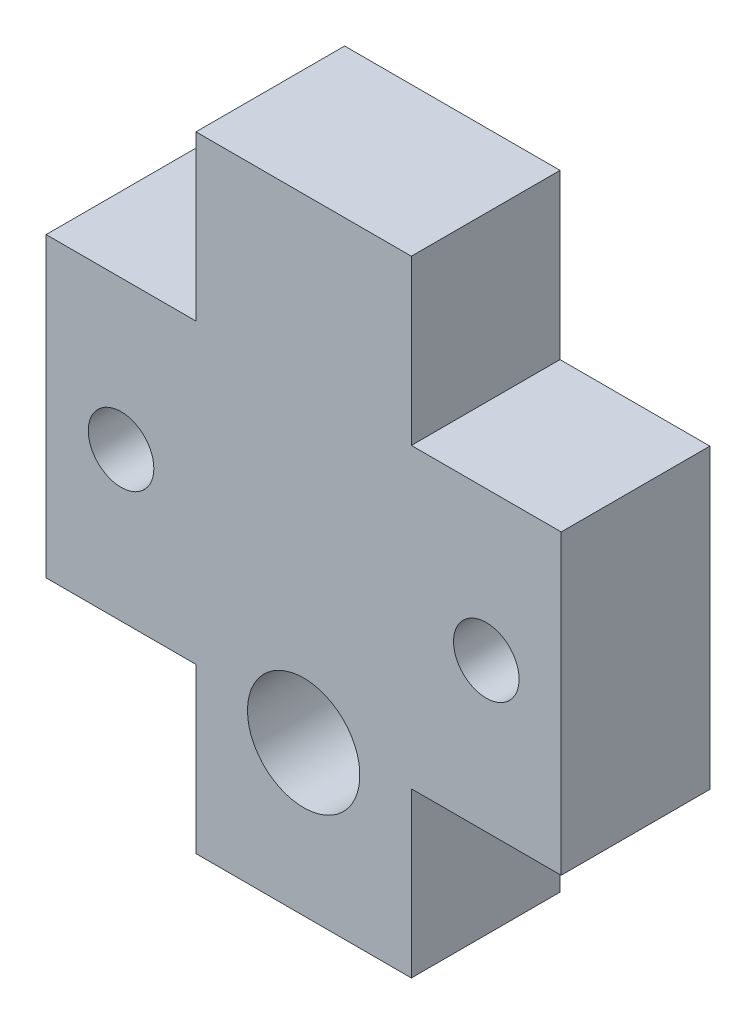
SolidWorks part; units mm, degrees
ref_plane "Front Plane" through (0, 0, 0) normal (0, 0, 1) x (1, 0, 0)
ref_plane "Top Plane" through (0, 0, 0) normal (0, 1, 0) x (1, 0, 0)
ref_plane "Right Plane" through (0, 0, 0) normal (1, 0, 0) x (0, 0, -1)
sketch "Sketch1" plane through (0, 0, 0) normal (0, 0, 1) x (1, 0, 0)
  line L0 (-11, 6.35) -> (-4.6, 6.35)
  line L1 (4.6, -13.35) -> (-4.6, -13.35)
  line L2 (4.6, -13.35) -> (4.6, 13.35)
  line L3 (4.6, 13.35) -> (-4.6, 13.35)
  line L4 (-4.6, -13.35) -> (-4.6, 13.35)
  line L5 (4.6, -13.35) -> (-4.6, 13.35) construction
  line L6 (4.6, 13.35) -> (-4.6, -13.35) construction
  line L7 (4.6, 6.35) -> (11, 6.35)
  line L9 (-4.6, -6.35) -> (-11, -6.35)
  line L10 (-11, 6.35) -> (-11, -6.35)
  line L13 (4.6, -6.35) -> (11, -6.35)
  line L14 (11, 6.35) -> (11, -6.35)
  circle A1 centre (-7.8, 0) radius 1.4
  circle A2 centre (7.8, 0) radius 1.4
  point P0 (0, 0)
  point P20 (-7.8, 6.35)
  point P21 (7.8, 6.35)
  point P22 (-11, 0)
  dimension "D7" = 2.8
  dimension "D1" = 7
  dimension "D2" = 12.7
  dimension "D3" = 22
  dimension "D4" = 6.4
extrude "Boss-Extrude1" add sketch "Sketch1" along normal blind 6.35
sketch "Sketch2" plane through (0, 0, 0) normal (0, 0, -1) x (-1, 0, 0)
  line L0 (-4.6, -13.35) -> (4.6, -13.35) construction
  circle A0 centre (0, -6.95) radius 2.4
  dimension "D1" = 4.8
  dimension "D2" = 6.4
extrude "Cut-Extrude1" cut sketch "Sketch2" against normal through all
